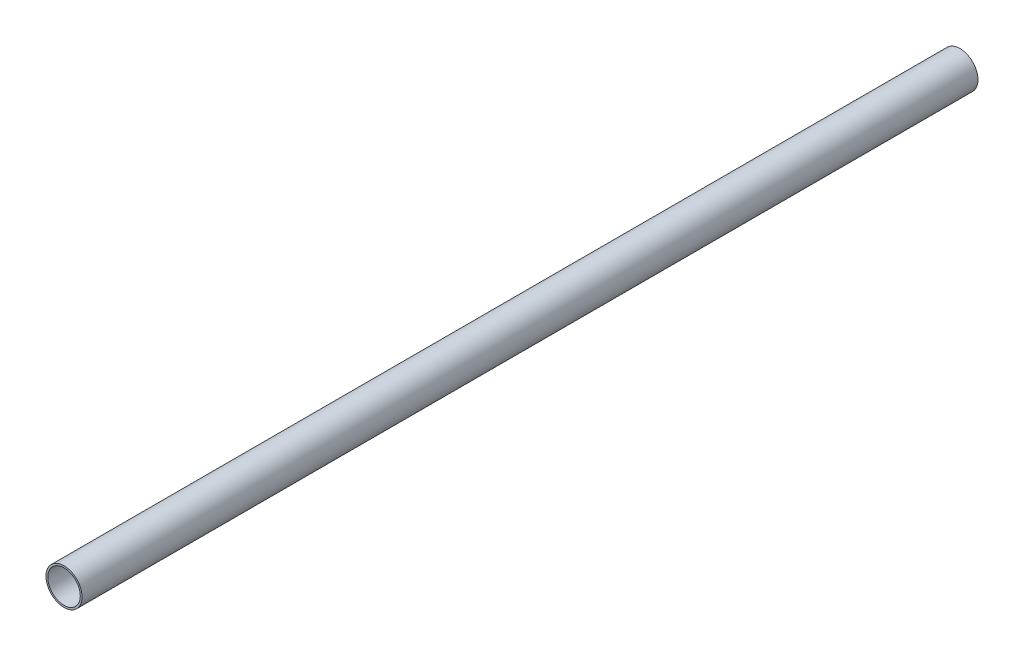
SolidWorks part; units mm, degrees
ref_plane "Front Plane" through (0, 0, 0) normal (0, 0, 1) x (1, 0, 0)
ref_plane "Top Plane" through (0, 0, 0) normal (0, 1, 0) x (1, 0, 0)
ref_plane "Right Plane" through (0, 0, 0) normal (1, 0, 0) x (0, 0, -1)
sketch "Sketch1" plane through (0, 0, 0) normal (0, 0, 1) x (1, 0, 0)
  circle A0 centre (0, 0) radius 10
  circle A1 centre (0, 0) radius 9
  dimension "D1" = 20
  dimension "D2" = 18
extrude "Boss-Extrude1" add sketch "Sketch1" along normal blind 496
